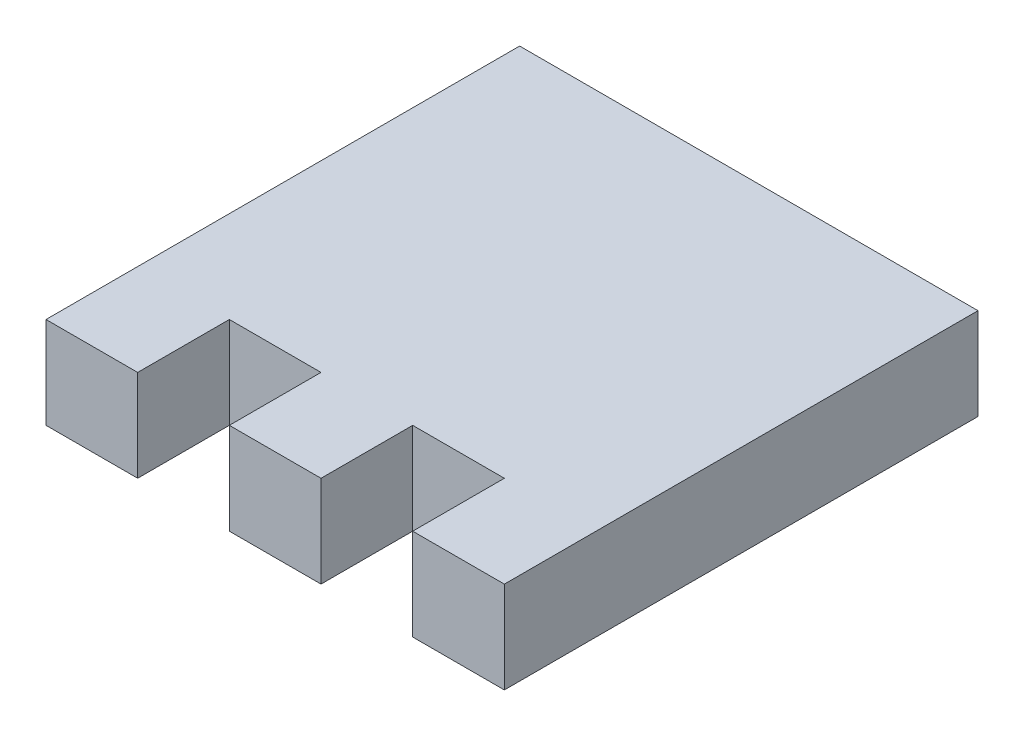
SolidWorks part; units mm, degrees
ref_plane "Front Plane" through (0, 0, 0) normal (0, 0, 1) x (1, 0, 0)
ref_plane "Top Plane" through (0, 0, 0) normal (0, 1, 0) x (1, 0, 0)
ref_plane "Right Plane" through (0, 0, 0) normal (1, 0, 0) x (0, 0, -1)
sketch "Sketch1" plane through (0, 0, 0) normal (0, 1, 0) x (1, 0, 0)
  line L0 (0, 7.75) -> (0, -7.75) construction
  line L1 (-7.5, -7.75) -> (-4.5, -7.75)
  line L2 (-7.5, -7.75) -> (-7.5, 7.75)
  line L3 (-7.5, 7.75) -> (7.5, 7.75)
  line L4 (7.5, -7.75) -> (7.5, 7.75)
  line L5 (-7.5, -7.75) -> (7.5, 7.75) construction
  line L6 (-7.5, 7.75) -> (7.5, -7.75) construction
  line L8 (-4.5, -7.75) -> (-4.5, -4.75)
  line L9 (-4.5, -4.75) -> (-1.5, -4.75)
  line L10 (-1.5, -7.75) -> (-1.5, -4.75)
  line L11 (4.5, -4.75) -> (1.5, -4.75)
  line L12 (1.5, -7.75) -> (1.5, -4.75)
  line L14 (4.5, -7.75) -> (4.5, -4.75)
  line L15 (-1.5, -7.75) -> (1.5, -7.75)
  line L16 (4.5, -7.75) -> (7.5, -7.75)
  point P0 (0, 0)
  dimension "D1" = 3
  dimension "D2" = 15.5
  dimension "D3" = 3
  dimension "D4" = 3
  dimension "D5" = 3
  dimension "D6" = 1.5
  dimension "D7" = 3
extrude "Boss-Extrude1" add sketch "Sketch1" along normal blind 3
